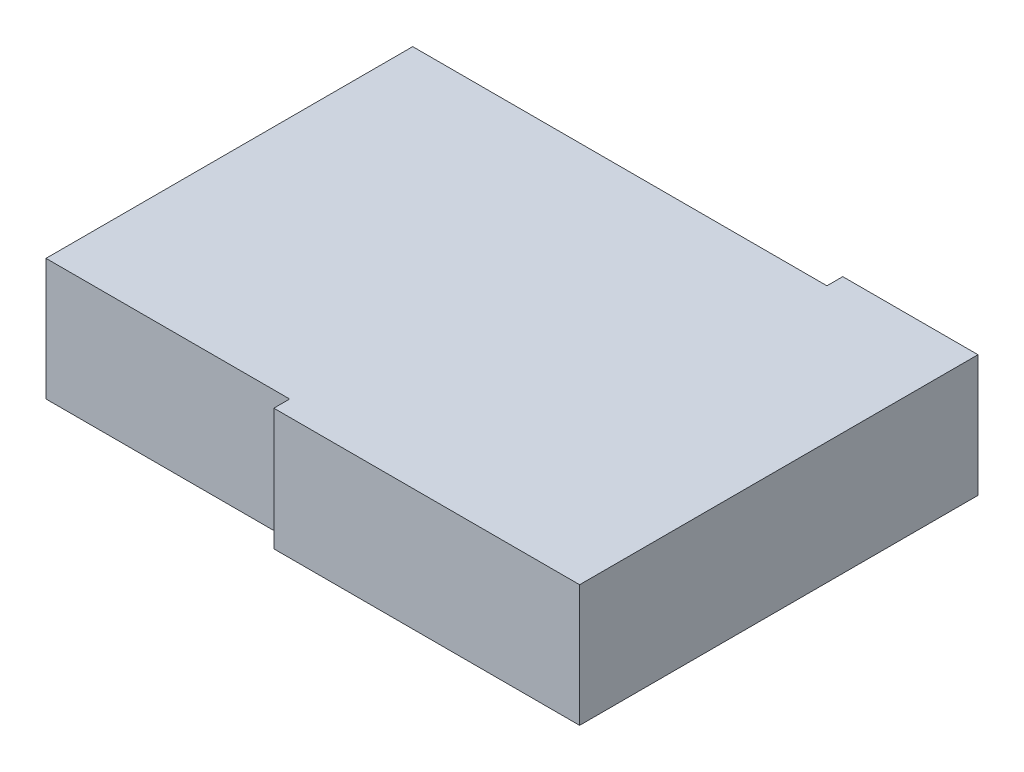
SolidWorks part; units mm, degrees
ref_plane "前视基准面" through (0, 0, 0) normal (0, 0, 1) x (1, 0, 0)
ref_plane "上视基准面" through (0, 0, 0) normal (0, 1, 0) x (1, 0, 0)
ref_plane "右视基准面" through (0, 0, 0) normal (1, 0, 0) x (0, 0, -1)
other "Configuration Table"
sketch "草图1" plane through (0, 0, 0) normal (0, 1, 0) x (1, 0, 0)
  line L0 (0, 0) -> (34, 0)
  line L1 (34, 0) -> (34, 1.3)
  line L2 (34, 1.3) -> (45.5, 1.3)
  line L3 (45.5, 1.3) -> (45.5, -31.8)
  line L4 (45.5, -31.8) -> (20, -31.8)
  line L5 (20, -31.8) -> (20, -30.5)
  line L6 (20, -30.5) -> (0, -30.5)
  line L7 (0, -30.5) -> (0, 0)
  line L8 (34.2, -0.2) -> (34.2, 1.1)
  line L9 (34.2, 1.1) -> (45.3, 1.1)
  line L10 (45.3, 1.1) -> (45.3, -31.6)
  line L11 (45.3, -31.6) -> (20.2, -31.6)
  line L12 (20.2, -31.6) -> (20.2, -30.3)
  line L13 (20.2, -30.3) -> (0.2, -30.3)
  line L14 (0.2, -30.3) -> (0.2, -0.2)
  line L15 (0.2, -0.2) -> (34.2, -0.2)
  dimension "D1" = 20
  dimension "D2" = 30.5
  dimension "D3" = 34
  dimension "D4" = 11.5
  dimension "D5" = 33.1
  dimension "D6" = 1.3
  dimension "D7" = 25.5
  dimension "D8" = 0.2
extrude "凸台-拉伸1" add sketch "草图1" along normal blind 10 contours L15 L14 L13 L12 L11 L10 L9 L8
